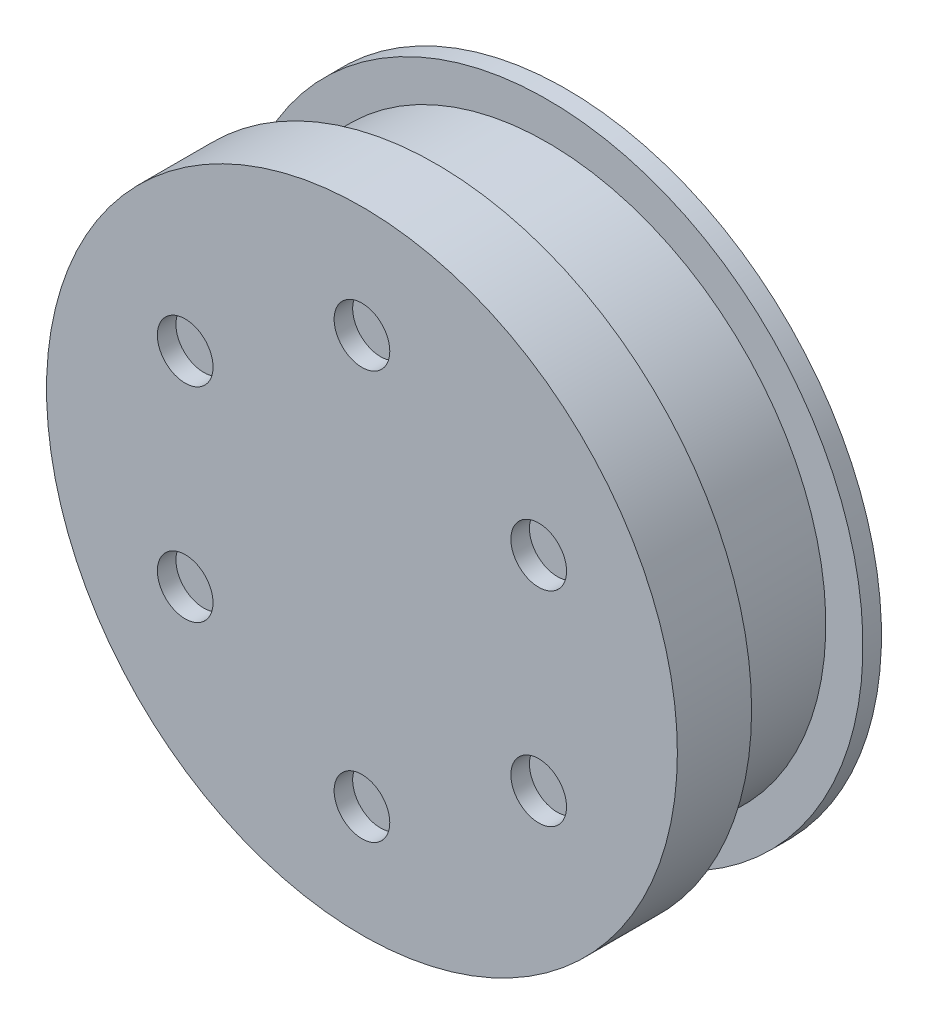
SolidWorks part; units mm, degrees
ref_plane "前视基准面" through (0, 0, 0) normal (0, 0, 1) x (1, 0, 0)
ref_plane "上视基准面" through (0, 0, 0) normal (0, 1, 0) x (1, 0, 0)
ref_plane "右视基准面" through (0, 0, 0) normal (1, 0, 0) x (0, 0, -1)
other "Configuration Table"
sketch "草图1" plane through (0, 0, 0) normal (0, 0, 1) x (1, 0, 0)
  circle A0 centre (0, 0) radius 15
extrude "凸台-拉伸1" add sketch "草图1" along normal blind 8
sketch "草图2" plane through (0, 0, 0) normal (0, 0, -1) x (-1, 0, 0)
  circle A0 centre (0, 0) radius 15
  circle A1 centre (0, 0) radius 17
  dimension "D1" = 2
extrude "凸台-拉伸2" add sketch "草图2" against normal blind 1
sketch "草图3" plane through (0, 0, 8) normal (0, 0, 1) x (1, 0, 0)
  circle A0 centre (0, 0) radius 11 construction
  circle A1 centre (0, 11) radius 1.5
  circle A2 centre (9.5263, 5.5) radius 1.5
  circle A3 centre (9.5263, -5.5) radius 1.5
  circle A4 centre (0, -11) radius 1.5
  circle A5 centre (-9.5263, -5.5) radius 1.5
  circle A6 centre (-9.5263, 5.5) radius 1.5
  point P17 (0, 0)
  dimension "D1" = 22
  dimension "D2" = 3
  dimension "D3" = 6
extrude "切除-拉伸1" cut sketch "草图3" against normal through all
sketch "草图4" plane through (0, 0, 8) normal (0, 0, 1) x (1, 0, 0)
  circle A0 centre (0, 0) radius 15
  circle A1 centre (0, 0) radius 17
  dimension "D1" = 2
extrude "凸台-拉伸3" add sketch "草图4" against normal blind 1
sketch "草图5" plane through (0, 0, 8) normal (0, 0, 1) x (1, 0, 0)
  circle A0 centre (0, 0) radius 17
extrude "凸台-拉伸4" add sketch "草图5" along normal blind 3
sketch "草图6" plane through (0, 0, 11) normal (0, 0, 1) x (1, 0, 0)
  circle A0 centre (0, 0) radius 11 construction
  circle A1 centre (0, 11) radius 1.5
  circle A2 centre (9.5263, 5.5) radius 1.5
  circle A3 centre (9.5263, -5.5) radius 1.5
  circle A4 centre (0, -11) radius 1.5
  circle A5 centre (-9.5263, -5.5) radius 1.5
  circle A6 centre (-9.5263, 5.5) radius 1.5
  point P18 (0, 0)
  dimension "D1" = 6
  dimension "D2" = 3
extrude "切除-拉伸6" cut sketch "草图6" against normal blind 1
